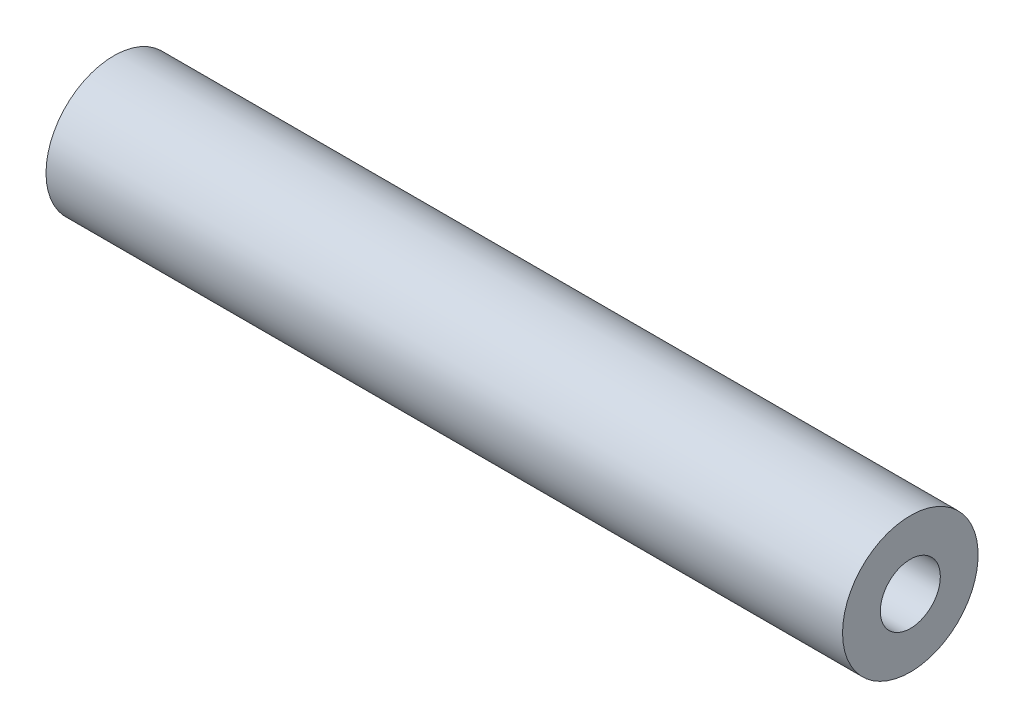
SolidWorks part; units mm, degrees
ref_plane "Front Plane" through (0, 0, 0) normal (0, 0, 1) x (1, 0, 0)
ref_plane "Top Plane" through (0, 0, 0) normal (0, 1, 0) x (1, 0, 0)
ref_plane "Right Plane" through (0, 0, 0) normal (1, 0, 0) x (0, 0, -1)
sketch "Sketch1" plane through (0, 0, 0) normal (1, 0, 0) x (0, 0, -1)
  circle A0 centre (0, 0) radius 5.08
  dimension "D1" = 10.16
extrude "Boss-Extrude1" add sketch "Sketch1" along normal blind 59.69
hole_wizard "#12-24 Tapped Hole1" positions "Sketch3" profile "Sketch2" tap size "#12-24" standard "ANSI Inch" end condition through all
sketch "Sketch3" plane through (59.69, 0, 0) normal (1, 0, 0) x (0, 0, -1)
  point P0 (0, 0)
sketch "Sketch2" plane through (59.69, 0, 0) normal (0, 1, 0) x (0, 0, -1)
  line L0 (0, 0) -> (0, 59.69)
  line L1 (0, 59.69) -> (2.2479, 59.69)
  line L2 (2.2479, 59.69) -> (2.2479, 0)
  line L5 (2.2479, 0) -> (0, 0)
  line L11 (0, -6.35) -> (0, 107.95) construction
  dimension "Thread Major Dia." = 4.4958
  dimension "Thru Tap Drill Depth" = 59.69
